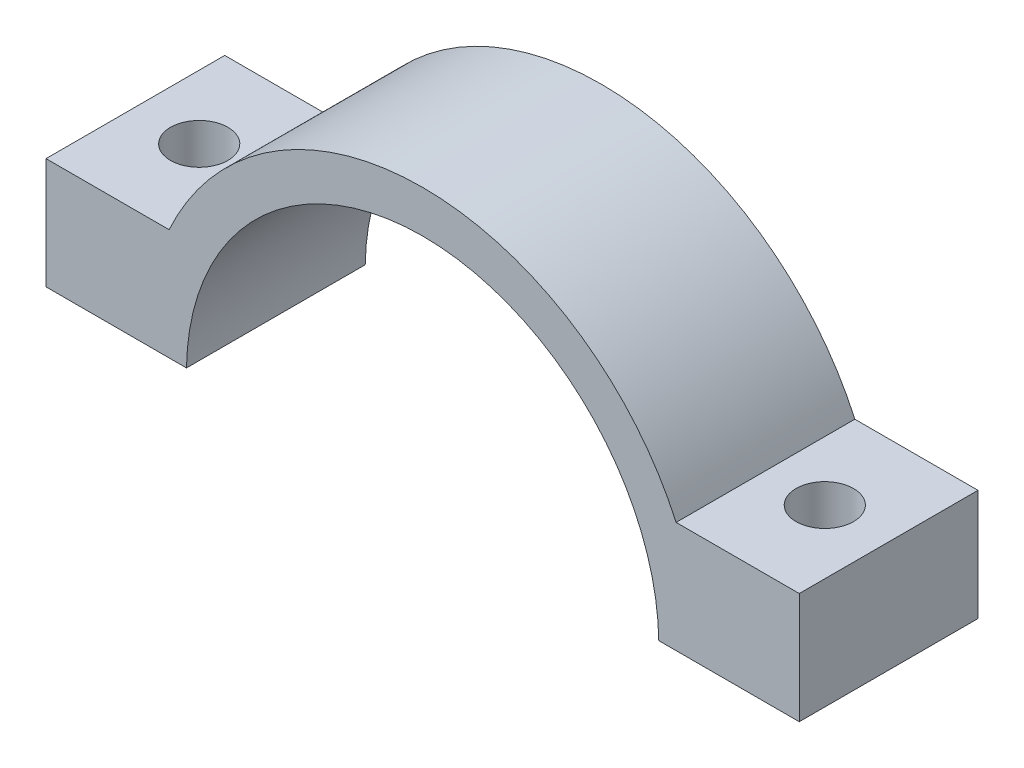
SolidWorks part; units mm, degrees
ref_plane "Front Plane" through (0, 0, 0) normal (0, 0, 1) x (1, 0, 0)
ref_plane "Top Plane" through (0, 0, 0) normal (0, 1, 0) x (1, 0, 0)
ref_plane "Right Plane" through (0, 0, 0) normal (1, 0, 0) x (0, 0, -1)
sketch "Split cap with raised flat washer seats profile" plane through (0, 0, 0) normal (0, 0, 1) x (1, 0, 0)
  line L0 (19.8555, 37.5) -> (29.5, 37.5)
  line L1 (29.5, 37.5) -> (29.5, 28.8)
  line L2 (29.5, 28.8) -> (18.4976, 28.8)
  line L3 (-18.4976, 28.8) -> (-29.5, 28.8)
  line L4 (-29.5, 28.8) -> (-29.5, 37.5)
  line L5 (-29.5, 37.5) -> (-19.8555, 37.5)
  arc A0 (-19.8555, 37.5) -> (19.8555, 37.5) centre (0, 28.5) cw
  arc A1 (18.4976, 28.8) -> (-18.4976, 28.8) centre (0, 28.5) ccw
extrude "Split cap with raised flat washer seats" add sketch "Split cap with raised flat washer seats profile" along normal blind 14
sketch "Sketch2" plane through (0, 0, 0) normal (0, 1, 0) x (1, 0, 0)
  circle A0 centre (-24.5, -7) radius 2.25
  circle A1 centre (24.5, -7) radius 2.25
extrude "M4 through holes" cut sketch "Sketch2" against normal through all and the other way through all
